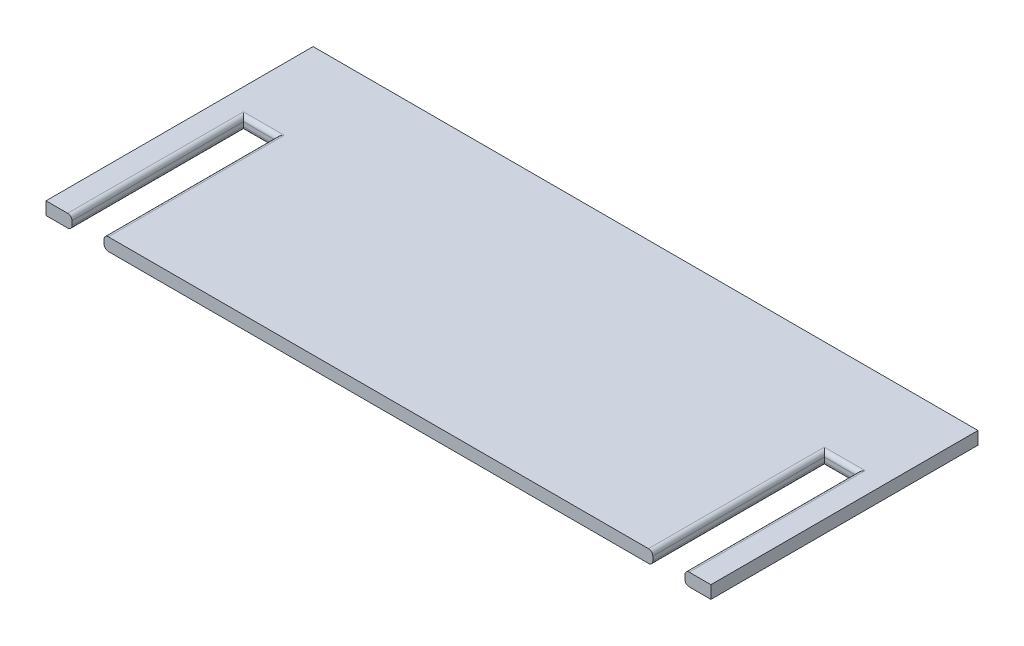
SolidWorks part; units mm, degrees
material "PLA"
ref_plane "Front Plane" through (0, 0, 0) normal (0, 0, 1) x (1, 0, 0)
ref_plane "Top Plane" through (0, 0, 0) normal (0, 1, 0) x (1, 0, 0)
ref_plane "Right Plane" through (0, 0, 0) normal (1, 0, 0) x (0, 0, -1)
sketch "Sketch1" plane through (0, 0, 0) normal (1, 0, 0) x (0, 0, -1)
  line L1 (-31.14, 1.49) -> (31.14, 1.49)
  line L2 (-31.14, 1.49) -> (-31.14, -1.49)
  line L3 (-31.14, -1.49) -> (31.14, -1.49)
  line L4 (31.14, 1.49) -> (31.14, -1.49)
  point P4 (0, 1.49)
  point P6 (-31.14, 0)
  dimension "D1" = 2.98
  dimension "D2" = 62.28
extrude "Boss-Extrude1" add sketch "Sketch1" along normal blind 155.03
sketch "Sketch2" plane through (0, 1.49, 0) normal (0, 1, 0) x (1, 0, 0)
  line L2 (1.0453, -31.14) -> (1.0453, 31.0177) construction
  line L4 (160.1625, 31.0777) -> (160.1625, -31.08) construction
  line L5 (1.0453, -31.14) -> (6.0453, -31.14) construction
  line L6 (16.0453, -26.1425) -> (16.0453, 31.2615) construction
  line L7 (6.0453, -31.14) -> (13.5453, -31.14)
  line L8 (6.0453, -31.14) -> (6.0453, 8.86)
  line L9 (6.0453, 8.86) -> (13.5453, 8.86)
  line L10 (13.5453, -31.14) -> (13.5453, 8.86)
  line L11 (155.03, -31.14) -> (0, -31.14) construction
  dimension "D1" = 5
  dimension "D2" = 2.5
  dimension "D3" = 40
  dimension "D4" = 0
  dimension "D5" = 7.5
extrude "Cut-Extrude1" cut sketch "Sketch2" against normal through all
fillet "Fillet1" radius 1 6 edges at (6.0453, -1.49, 11.14) (9.7953, -1.49, -8.86) (13.5453, -1.49, 11.14) (13.5453, 1.49, 11.14) (9.7953, 1.49, -8.86) (6.0453, 1.49, 11.14)
ref_plane "Plane1" through (77.515, 0, 0) normal (1, 0, 0) x (0, 0, -1)
mirror "Mirror1" about plane through (77.515, 0, 0) normal (1, 0, 0) of "Cut-Extrude1", "Fillet1"
